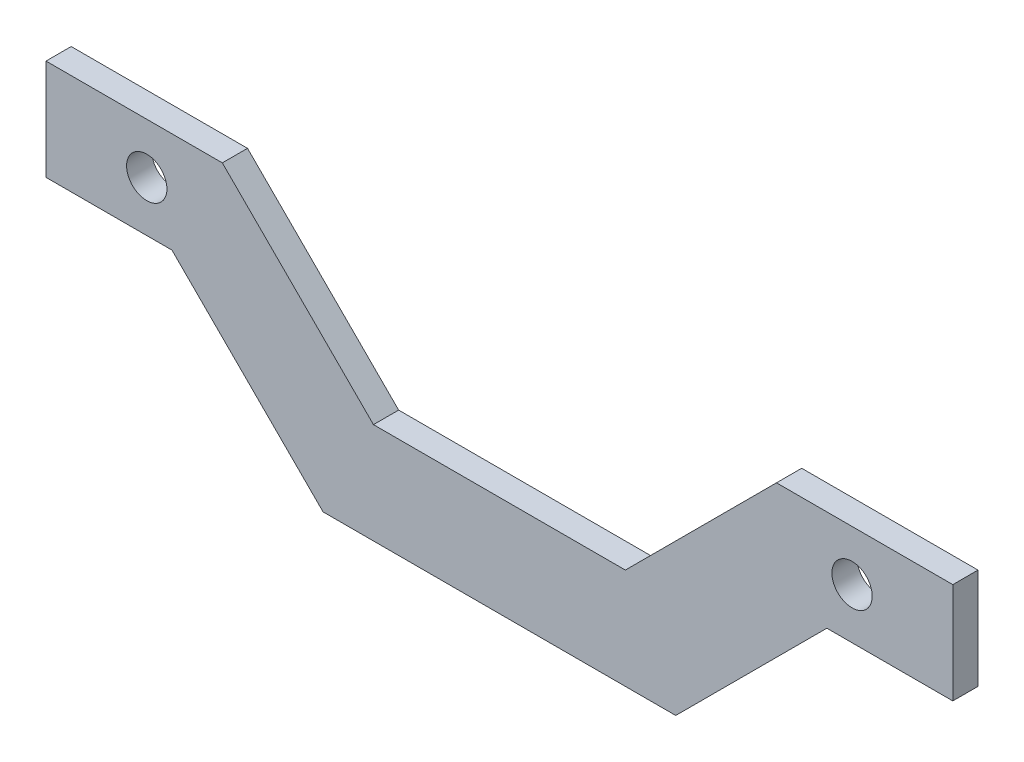
SolidWorks part; units mm, degrees
ref_plane "前视基准面" through (0, 0, 0) normal (0, 0, 1) x (1, 0, 0)
ref_plane "上视基准面" through (0, 0, 0) normal (0, 1, 0) x (1, 0, 0)
ref_plane "右视基准面" through (0, 0, 0) normal (1, 0, 0) x (0, 0, -1)
sketch "草图1" plane through (0, 0, 0) normal (0, 0, 1) x (1, 0, 0)
  line L0 (0, 0) -> (0, 20) construction
  line L1 (35, 0) -> (-35, 0)
  line L2 (-35, 0) -> (-65, 30)
  line L3 (-65, 30) -> (-90, 30)
  line L4 (-90, 30) -> (-90, 50)
  line L5 (-90, 50) -> (-55, 50)
  line L6 (-55, 50) -> (-25, 20)
  line L7 (-25, 20) -> (25, 20)
  line L8 (55, 50) -> (25, 20)
  line L9 (90, 50) -> (55, 50)
  line L10 (90, 30) -> (90, 50)
  line L11 (65, 30) -> (90, 30)
  line L12 (35, 0) -> (65, 30)
  circle A0 centre (-78.182, 40) radius 8 construction
  circle A1 centre (78.182, 40) radius 8 construction
  point P14 (-90, 40)
  dimension "D3" = 16
  dimension "D1" = 180
  dimension "D2" = 135
  dimension "D4" = 20
  dimension "D5" = 20
  dimension "D6" = 35
  dimension "D7" = 25
  dimension "D8" = 70
extrude "凸台-拉伸1" add sketch "草图1" along normal blind 5
sketch "草图2" plane through (0, 0, 0) normal (0, 0, -1) x (-1, 0, 0)
  line L0 (90, 50) -> (90, 30) construction
  line L1 (55, 50) -> (90, 50) construction
  line L2 (0, 0) -> (0, 20) construction
  line L3 (35, 0) -> (-35, 0) construction
  line L4 (-25, 20) -> (25, 20) construction
  circle A0 centre (70, 40) radius 4
  circle A1 centre (-70, 40) radius 4
  dimension "D1" = 8
  dimension "D2" = 20
  dimension "D3" = 10
extrude "切除-拉伸1" cut sketch "草图2" against normal blind 10
